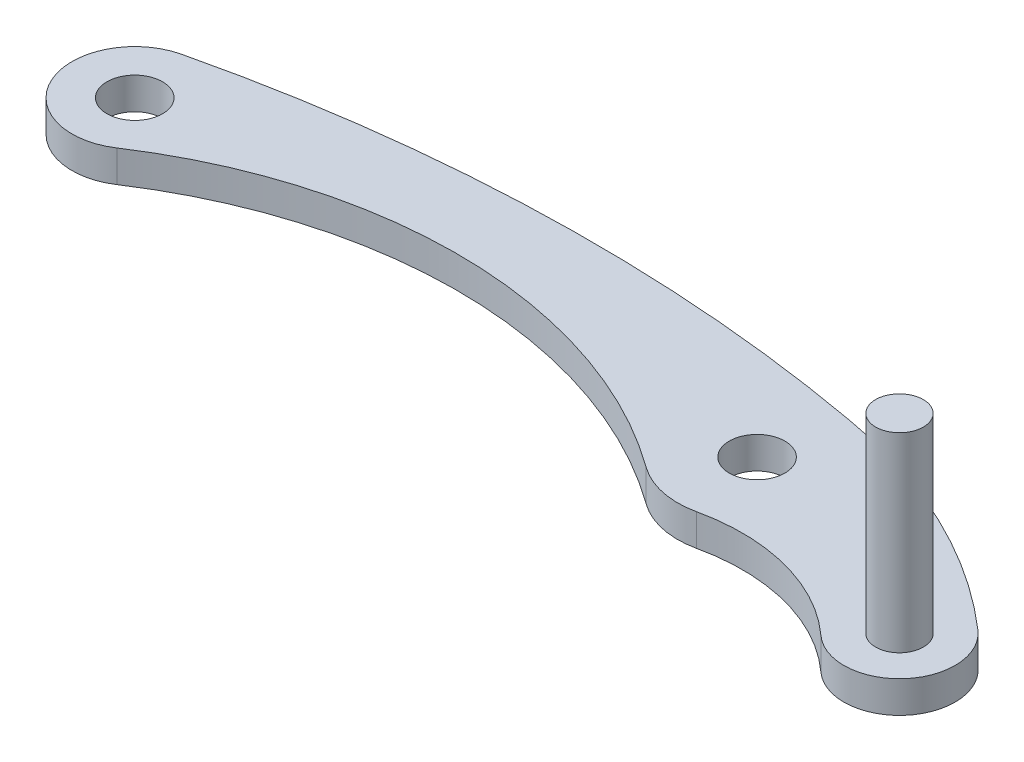
SolidWorks part; units mm, degrees
ref_plane "Front Plane" through (0, 0, 0) normal (0, 0, 1) x (1, 0, 0)
ref_plane "Top Plane" through (0, 0, 0) normal (0, 1, 0) x (1, 0, 0)
ref_plane "Right Plane" through (0, 0, 0) normal (1, 0, 0) x (0, 0, -1)
sketch "Sketch1" plane through (0, 0, 0) normal (0, 1, 0) x (1, 0, 0)
  line L0 (0, 25.5178) -> (0, -32.2544) construction
  line L1 (0, 0) -> (39.1784, 0) construction
  line L2 (39.1784, 0) -> (88.4884, 0) construction
  line L4 (39.1784, 0) -> (78.5826, -14.3419) construction
  arc A0 (-0.9109, 3.8435) -> (2.1717, -3.2995) centre (0, 0) ccw
  arc A2 (2.1717, -3.2995) -> (36.248, -4.0512) centre (18.6653, -28.3586) cw
  arc A3 (-0.9109, 3.8435) -> (40.0578, 4.9221) centre (22.1493, -93.4613) cw
  circle A4 centre (0, 0) radius 1.75
  circle A5 centre (39.1784, 0) radius 1.75
  arc A8 (36.248, -4.0512) -> (40.2575, -4.8822) centre (39.1784, 0) ccw
  circle A9 centre (53.2738, -5.1303) radius 3.5
  arc A10 (40.0578, 4.9221) -> (55.5761, -2.4941) centre (34.5264, -26.5962) cw
  arc A11 (40.2575, -4.8822) -> (50.9194, -7.7201) centre (42.8474, -16.5994) cw
  dimension "D2" = 7.9
  dimension "D3" = 10
  dimension "D4" = 100
  dimension "D5" = 30
  dimension "D6" = 3.5
  dimension "D7" = 3.5
  dimension "D8" = 200
  dimension "D10" = 12
  dimension "D9" = 7
  dimension "D11" = 32
  dimension "D1" = 39.1784
  dimension "D12" = 15
extrude "Boss-Extrude3" add sketch "Sketch1" along normal blind 2 contours A8 A11 A9 A10 A3 A0 A2 A4 A5 | A9
sketch "Sketch3" plane through (0, 2, 0) normal (0, 1, 0) x (1, 0, 0)
  circle A0 centre (53.2738, -5.1303) radius 1.5
  dimension "D1" = 3
extrude "Boss-Extrude4" add sketch "Sketch3" along normal blind 12
